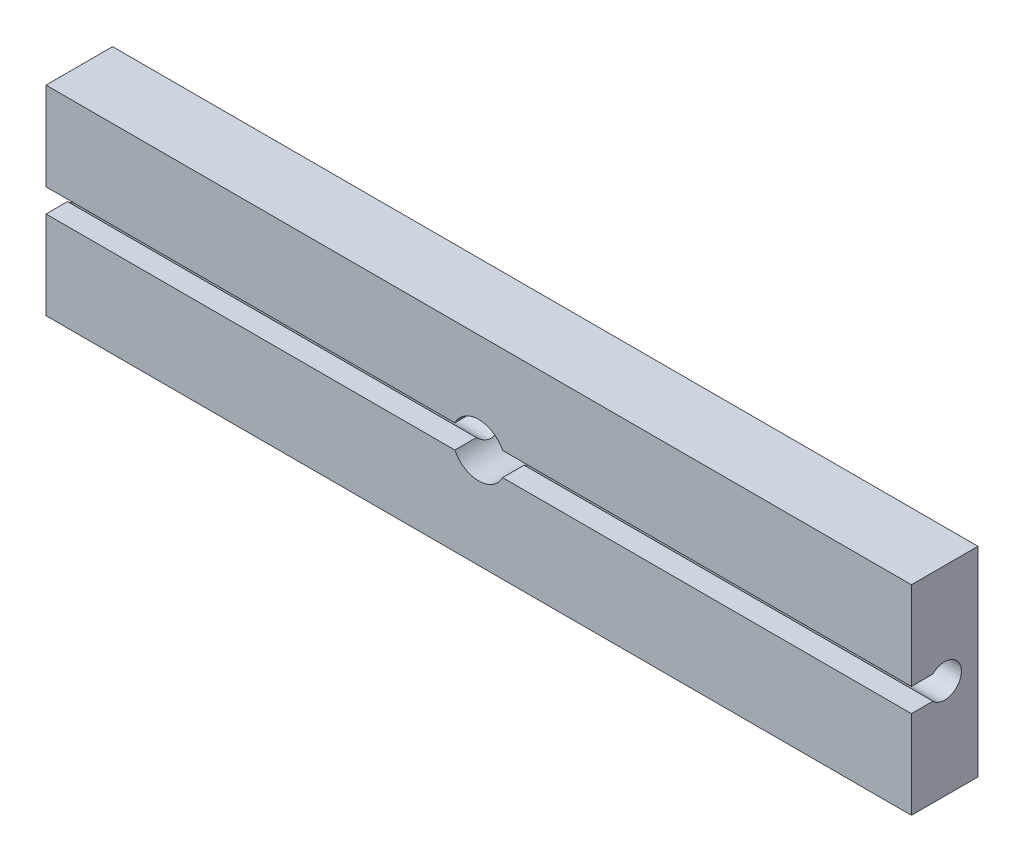
SolidWorks part; units mm, degrees
ref_plane "前视基准面" through (0, 0, 0) normal (0, 0, 1) x (1, 0, 0)
ref_plane "上视基准面" through (0, 0, 0) normal (0, 1, 0) x (1, 0, 0)
ref_plane "右视基准面" through (0, 0, 0) normal (1, 0, 0) x (0, 0, -1)
sketch "草图1" plane through (0, 0, 0) normal (0, 0, 1) x (1, 0, 0)
  line L0 (0, 0) -> (0, 50000) construction
  line L1 (0, 0) -> (50000, 0) construction
  line L3 (-65, 15) -> (65, 15)
  line L4 (-65, 15) -> (-65, -15)
  line L5 (-65, -15) -> (65, -15)
  line L6 (65, 15) -> (65, -15)
  circle A0 centre (-50, 0) radius 15
  circle A1 centre (50, 0) radius 15
  circle A2 centre (0, 0) radius 4
  dimension "D3" = 15
  dimension "D1" = 130
  dimension "D2" = 30
extrude "凸台-拉伸2" add sketch "草图1" along normal blind 10 contours L5 A1 L3 A0 A2 | A0 | A1
sketch "草图2" plane through (0, 0, 10) normal (0, 0, 1) x (1, 0, 0)
  line L0 (0, 0) -> (50000, 0) construction
  line L1 (0, 0) -> (0, 50000) construction
  line L2 (-50, -8) -> (50, -8)
  line L3 (-50, 12) -> (50, 12)
  line L4 (-50, 12) -> (-50, 8)
  line L5 (-50, 8) -> (50, 8)
  line L6 (50, 12) -> (50, 8)
  line L7 (50, -12) -> (50, -8)
  line L8 (-50, -12) -> (50, -12)
  line L9 (-50, -12) -> (-50, -8)
  line L10 (-50, 15) -> (-50, -15)
  line L11 (50, 15) -> (50, -15)
  line L12 (-2, -8) -> (2, -8)
  line L13 (-2, 12) -> (2, 12)
  line L14 (-2, 12) -> (-2, 8)
  line L15 (-2, 8) -> (2, 8)
  line L16 (2, 12) -> (2, 8)
  line L17 (2, -12) -> (2, -8)
  line L18 (-2, -12) -> (2, -12)
  line L19 (-2, -12) -> (-2, -8)
  dimension "D1" = 4
  dimension "D2" = 24
  dimension "D3" = 0
  dimension "D4" = 2
extrude "切除-拉伸3" cut sketch "草图2" against normal through all contours L3 L16 L5 L6 | L14 L3 L4 L5 | L8 L19 L2 L9 | L17 L8 L7 L2
sketch "草图3" plane through (0, 0, 10) normal (0, 0, 1) x (1, 0, 0)
  line L0 (-50, 12) -> (-50, -12)
  line L1 (50, 12) -> (50, -12)
  line L2 (-50, 0) -> (49950, 0) construction
  line L3 (-50, 2) -> (50, 2)
  line L5 (-50, -2) -> (50, -2)
  circle A0 centre (0, 0) radius 4
  point P14 (-50, 0)
  circle M10 centre (0, 0) radius 4
  dimension "D1" = 4
extrude "切除-拉伸4" cut sketch "草图3" against normal through all contours L0 L2 A0 L3 | L2 L0 L5 M10 | L2 A0 L5 L1 | L2 L1 L3 M10
sketch "草图4" plane through (0, 0, 10) normal (0, 0, 1) x (1, 0, 0)
  line L1 (2, 12) -> (50, 12)
  line L2 (2, 12) -> (2, 8)
  line L3 (2, 8) -> (50, 8)
  line L4 (50, 12) -> (50, 8)
  line L5 (50, -8) -> (2, -8)
  line L6 (50, -8) -> (50, -12)
  line L7 (50, -12) -> (2, -12)
  line L8 (2, -8) -> (2, -12)
  line L9 (-2, 12) -> (-50, 12)
  line L10 (-2, 12) -> (-2, 8)
  line L11 (-2, 8) -> (-50, 8)
  line L12 (-50, 12) -> (-50, 8)
  line L13 (-50, -8) -> (-2, -8)
  line L14 (-50, -8) -> (-50, -12)
  line L15 (-50, -12) -> (-2, -12)
  line L16 (-2, -8) -> (-2, -12)
extrude "凸台-拉伸3" add sketch "草图4" against normal blind 10
sketch "草图5" plane through (-50, 0, 0) normal (1, 0, 0) x (0, 0, -1)
  line L1 (-10, 2) -> (0, 2)
  line L2 (-10, 2) -> (-10, -2)
  line L3 (-10, -2) -> (0, -2)
  line L4 (0, 2) -> (0, -2)
extrude "凸台-拉伸4" add sketch "草图5" along normal blind 100
sketch "草图6" plane through (0, -15, 0) normal (0, -1, 0) x (1, 0, 0)
  line L1 (-50, 10) -> (-65, 10)
  line L2 (-50, 10) -> (-50, 0)
  line L3 (-50, 0) -> (-65, 0)
  line L4 (-65, 10) -> (-65, 0)
extrude "切除-拉伸5" cut sketch "草图6" against normal blind 100
sketch "草图7" plane through (-50, 0, 0) normal (-1, 0, 0) x (0, 0, 1)
  line L0 (0, 0) -> (0, 50000) construction
  line L1 (0, 15) -> (0, -15) construction
  line L2 (0, 0) -> (50000, 0) construction
  line L3 (5, 15) -> (5, -49985) construction
  line L4 (10, 15) -> (0, 15) construction
  circle A0 centre (5, 0) radius 2.5
  point P4 (0, 0)
  point P11 (5, 15)
extrude "切除-拉伸14" cut sketch "草图7" against normal through all contours A0
sketch "草图11" plane through (0, 0, 10) normal (0, 0, 1) x (1, 0, 0)
  circle A0 centre (0, 0) radius 4
extrude "切除-拉伸15" cut sketch "草图11" against normal through all
sketch "草图12" plane through (0, 0, 10) normal (0, 0, 1) x (1, 0, 0)
  line L0 (-50, 15) -> (-50, -15) construction
  circle A0 centre (-50, 0) radius 15
extrude "凸台-拉伸5" add sketch "草图12" against normal blind 10
sketch "草图14" plane through (0, 15, 0) normal (0, 1, 0) x (1, 0, 0)
  line L1 (-50, 0) -> (50, 0)
  line L2 (-50, 0) -> (-50, -10)
  line L3 (-50, -10) -> (50, -10)
  line L4 (50, 0) -> (50, -10)
extrude "凸台-拉伸6" add sketch "草图14" against normal blind 30
sketch "草图15" plane through (50, 0, 0) normal (1, 0, 0) x (0, 0, -1)
  circle A0 centre (-5, 0) radius 2.5
extrude "切除-拉伸16" cut sketch "草图15" against normal through all
sketch "草图16" plane through (0, 0, 10) normal (0, 0, 1) x (1, 0, 0)
  circle A0 centre (0, 0) radius 4
extrude "切除-拉伸17" cut sketch "草图16" against normal through all
sketch "草图17" plane through (0, 0, 10) normal (0, 0, 1) x (1, 0, 0)
  line L1 (50, 15) -> (65, 15)
  line L2 (50, 15) -> (50, -15)
  line L3 (50, -15) -> (65, -15)
  line L4 (65, 15) -> (65, -15)
  line L5 (-50, 15) -> (-65, 15)
  line L6 (-50, 15) -> (-50, -15)
  line L7 (-50, -15) -> (-65, -15)
  line L8 (-65, 15) -> (-65, -15)
  arc A0 (50, -15) -> (50, 15) centre (50, 0) ccw construction
  arc A1 (-50, 15) -> (-50, -15) centre (-50, 0) ccw construction
extrude "凸台-拉伸7" add sketch "草图17" against normal blind 10
sketch "草图18" plane through (-65, 0, 0) normal (-1, 0, 0) x (0, 0, 1)
  line L0 (5, -15) -> (5, 49985) construction
  line L1 (0, -15) -> (10, -15) construction
  line L2 (0, 0) -> (50000, 0) construction
  line L3 (0, 15) -> (0, -15) construction
  circle A0 centre (5, 0) radius 2.5
  point P4 (5, -15)
  point P9 (0, 0)
extrude "切除-拉伸18" cut sketch "草图18" against normal through all contours A0
sketch "草图19" plane through (-65, 0, 0) normal (-1, 0, 0) x (0, 0, 1)
  line L0 (0, 0) -> (50000, 0) construction
  line L1 (5, 15) -> (5, -49985) construction
  line L2 (0, 15) -> (10, 15) construction
  line L3 (5, 0) -> (10, 5)
  line L4 (10, 15) -> (10, -15) construction
  line L5 (5, 0) -> (10, -5)
  line L6 (6.7678, 1.7678) -> (10, 1.7678)
  line L7 (6.7678, -1.7678) -> (10, -1.7678)
  line L8 (10, -1.7678) -> (10, 1.7678)
  circle A0 centre (5, 0) radius 2.5 construction
  circle A1 centre (5, 0) radius 2.5
  point P7 (5, 15)
  circle M1 centre (5, 0) radius 2.5
  line M4 (10, -15) -> (10, 15)
extrude "切除-拉伸19" cut sketch "草图19" against normal through all contours L7 L6 M1 M4
